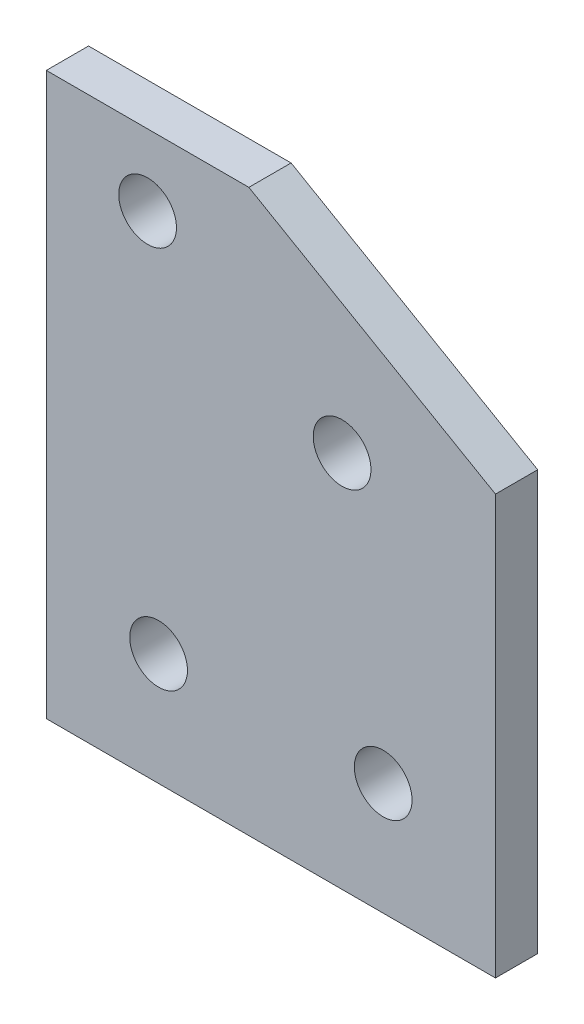
SolidWorks part; units mm, degrees
ref_plane "Front Plane" through (0, 0, 0) normal (0, 0, 1) x (1, 0, 0)
ref_plane "Top Plane" through (0, 0, 0) normal (0, 1, 0) x (1, 0, 0)
ref_plane "Right Plane" through (0, 0, 0) normal (1, 0, 0) x (0, 0, -1)
sketch "Sketch1" plane through (0, 0, 0) normal (0, 0, 1) x (1, 0, 0)
  line L0 (-25.4, -31.75) -> (25.4, -31.75)
  line L1 (25.4, -31.75) -> (25.4, 15.6464)
  line L2 (25.4, 15.6464) -> (-2.4892, 31.75)
  line L3 (-2.4892, 31.75) -> (-25.4, 31.75)
  line L4 (-25.4, 31.75) -> (-25.4, -31.75)
  line L5 (8.0521, 10.9982) -> (-13.9449, 23.6982) construction
  line L6 (0, 0) -> (0, 31.75) construction
  line L7 (0, 0) -> (25.4, 0) construction
  line L8 (0, 0) -> (0, -31.75) construction
  line L9 (0, 0) -> (-25.4, 0) construction
  circle A0 centre (-13.9449, 23.6982) radius 3.2639
  circle A1 centre (8.0521, 10.9982) radius 3.2639
  circle A2 centre (12.7, -19.05) radius 3.2639
  circle A3 centre (-12.7, -19.05) radius 3.2639
  point P20 (25.4, -6.35)
  dimension "E" = 6.5278
  dimension "H" = 22.9108
  dimension "Length (A)" = 63.5
  dimension "B" = 50.8
  dimension "D" = 12.7
  dimension "C" = 25.4
  dimension "G" = 47.3964
  dimension "J" = 30.0482
  dimension "For Rail Connection Angle (K)" = 30
  dimension "D1" = 12.7
  dimension "D2" = 25.4
  dimension "D3" = 12.7
  dimension "For Rail Height" = 25.4
sketch "Sketch2" plane through (0, 0, 0) normal (1, 0, 0) x (0, 0, -1)
  line L0 (-2.3876, 0) -> (2.3876, 0) construction
  line L1 (-2.3876, 23.6982) -> (10.3124, 23.6982) construction
  line L2 (10.3124, 26.8732) -> (10.3124, 20.5232) construction
  line L3 (10.3124, 26.8732) -> (9.0424, 26.8732) construction
  dimension "F" = 4.7752
  dimension "Mounting Fastener Thread Length" = 12.7
  dimension "Mounting Fastener Thread Size" = 6.35
  dimension "Mounting Fastener Thread Pitch" = 1.27
sketch "Sketch3" plane through (0, 0, 0) normal (0, 0, 1) x (1, 0, 0)
  line L0 (25.4, -31.75) -> (25.4, 15.6464) construction
  line L1 (-25.4, -31.75) -> (25.4, -31.75) construction
  line L2 (-25.4, 31.75) -> (-25.4, -31.75) construction
  line L3 (-2.4892, 31.75) -> (-25.4, 31.75) construction
  line L4 (25.4, 15.6464) -> (-2.4892, 31.75) construction
  line L5 (25.4, -31.75) -> (25.4, 15.6464)
  line L6 (-25.4, -31.75) -> (25.4, -31.75)
  line L7 (-25.4, 31.75) -> (-25.4, -31.75)
  line L8 (-2.4892, 31.75) -> (-25.4, 31.75)
  line L9 (25.4, 15.6464) -> (-2.4892, 31.75)
  circle A0 centre (12.7, -19.05) radius 3.2639 construction
  circle A1 centre (8.0521, 10.9982) radius 3.2639 construction
  circle A2 centre (-12.7, -19.05) radius 3.2639 construction
  circle A3 centre (-13.9449, 23.6982) radius 3.2639 construction
  circle A4 centre (12.7, -19.05) radius 3.2639
  circle A5 centre (8.0521, 10.9982) radius 3.2639
  circle A6 centre (-12.7, -19.05) radius 3.2639
  circle A7 centre (-13.9449, 23.6982) radius 3.2639
extrude "Boss-Extrude1" add sketch "Sketch3" along normal up to vertex (2.3876 mm away) and the other way up to vertex (2.3876 mm away) up to point (0, 0, 2.3876) other way up to point (0, 0, -2.3876)
equation "\"D1@Sketch1\"=\"C@Sketch1\"/2"
equation "\"D2@Sketch1\"=\"C@Sketch1\""
equation "\"D3@Sketch1\"=\"D@Sketch1\""
